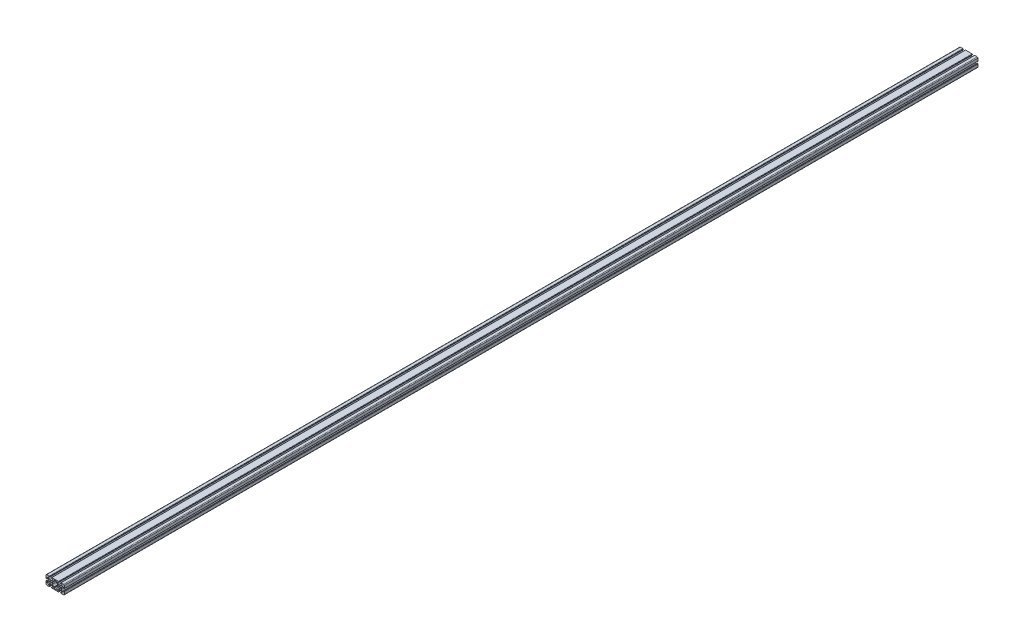
SolidWorks part; units mm, degrees
material "6061 Alloy"
ref_plane "Front Plane" through (0, 0, 0) normal (0, 0, 1) x (1, 0, 0)
ref_plane "Top Plane" through (0, 0, 0) normal (0, 1, 0) x (1, 0, 0)
ref_plane "Right Plane" through (0, 0, 0) normal (1, 0, 0) x (0, 0, -1)
sketch "Sketch1" plane through (0, 0, 0) normal (0, 0, 1) x (1, 0, 0)
  line L0 (-14.3719, 20) -> (14.3719, 20)
  line L1 (-15.94, 17.1729) -> (-15.94, 18.3529)
  line L2 (-11.285, 15.68) -> (-14.37, 15.68)
  line L3 (-9.715, 13.6545) -> (-9.715, 14.11)
  line L4 (4.0718, 15.68) -> (-4.0718, 15.68)
  line L5 (-5.3418, 14.41) -> (-5.3418, 12.1296)
  line L6 (-5.7137, 11.2316) -> (-10.5988, 6.3465)
  line L7 (-12.2841, 3.2591) -> (-12.2841, -2.725)
  line L8 (5.991, -20) -> (-1.7801, -20)
  line L9 (0, 20) -> (0, -25.1394) construction
  line L10 (-4.0718, -15.68) -> (4.0718, -15.68)
  line L11 (-5.3418, -12.1296) -> (-5.3418, -14.41)
  line L12 (-11.2012, -5.7441) -> (-5.7137, -11.2316)
  line L13 (-42.275, 0) -> (43.1806, 0) construction
  line L14 (-9.9376, 13.1171) -> (-14.0919, 8.9628)
  line L15 (-17.4506, 7.7) -> (-22.5494, 7.7)
  line L16 (-25.9081, 8.9628) -> (-30.0624, 13.1171)
  line L17 (-30.285, 13.6545) -> (-30.285, 14.11)
  line L18 (-28.715, 15.68) -> (-25.63, 15.68)
  line L19 (-24.06, 17.25) -> (-24.06, 18.4312)
  line L20 (-25.5696, 20) -> (-33, 20)
  line L21 (-33, 20) -> (-36.83, 20)
  line L22 (-40, 16.8406) -> (-40, 13.0106)
  line L23 (-40, 13.0106) -> (-40, 5.5825)
  line L24 (-38.3243, 4.06) -> (-37.1443, 4.06)
  line L25 (-35.68, 5.6264) -> (-35.68, 8.7114)
  line L26 (-34.11, 10.2814) -> (-33.6509, 10.2814)
  line L27 (-33.1135, 10.0588) -> (-29.0111, 5.9564)
  line L28 (-27.7159, 2.571) -> (-27.7159, -2.502)
  line L29 (-28.9155, -5.8608) -> (-33.1719, -10.1172)
  line L30 (-33.7093, -10.3398) -> (-34.111, -10.3398)
  line L31 (-35.68, -8.715) -> (-35.68, -5.63)
  line L32 (-37.25, -4.06) -> (-38.43, -4.06)
  line L33 (-40, -5.5696) -> (-40, -13)
  line L34 (-40, -13) -> (-40, -16.83)
  line L35 (-37.0574, -20) -> (-33.2274, -20)
  line L36 (-33.2274, -20) -> (-25.797, -20)
  line L37 (-24.06, -18.4389) -> (-24.06, -17.25)
  line L38 (-25.63, -15.68) -> (-28.715, -15.68)
  line L39 (-30.285, -14.11) -> (-30.285, -13.6545)
  line L40 (-30.0624, -13.1171) -> (-26.3095, -9.3642)
  line L41 (-23.3415, -7.7) -> (-16.6585, -7.7)
  line L42 (-13.6905, -9.3642) -> (-9.9376, -13.1171)
  line L43 (-9.715, -13.6545) -> (-9.715, -14.11)
  line L44 (-11.285, -15.68) -> (-14.37, -15.68)
  line L45 (-15.94, -17.25) -> (-15.94, -18.43)
  line L46 (-14.37, -20) -> (-5.991, -20)
  line L47 (-5.991, -20) -> (-1.7801, -20)
  line L48 (14.37, -20) -> (5.991, -20)
  line L49 (15.94, -17.25) -> (15.94, -18.43)
  line L50 (11.285, -15.68) -> (14.37, -15.68)
  line L51 (9.715, -13.6545) -> (9.715, -14.11)
  line L52 (13.6905, -9.3642) -> (9.9376, -13.1171)
  line L53 (23.3415, -7.7) -> (16.6585, -7.7)
  line L54 (30.0624, -13.1171) -> (26.3095, -9.3642)
  line L55 (30.285, -14.11) -> (30.285, -13.6545)
  line L56 (25.63, -15.68) -> (28.715, -15.68)
  line L57 (24.06, -18.4389) -> (24.06, -17.25)
  line L58 (33.2274, -20) -> (25.797, -20)
  line L59 (37.0574, -20) -> (33.2274, -20)
  line L60 (40, -13) -> (40, -16.83)
  line L61 (40, -5.5696) -> (40, -13)
  line L62 (37.25, -4.06) -> (38.43, -4.06)
  line L63 (35.68, -8.715) -> (35.68, -5.63)
  line L64 (33.7093, -10.3398) -> (34.111, -10.3398)
  line L65 (28.9155, -5.8608) -> (33.1719, -10.1172)
  line L66 (27.7159, 2.571) -> (27.7159, -2.502)
  line L67 (33.1135, 10.0588) -> (29.0111, 5.9564)
  line L68 (34.11, 10.2814) -> (33.6509, 10.2814)
  line L69 (35.68, 5.6264) -> (35.68, 8.7114)
  line L70 (38.3243, 4.06) -> (37.1443, 4.06)
  line L71 (40, 13.0106) -> (40, 5.5825)
  line L72 (40, 16.8406) -> (40, 13.0106)
  line L73 (33, 20) -> (36.83, 20)
  line L74 (25.5696, 20) -> (33, 20)
  line L75 (24.06, 17.25) -> (24.06, 18.4312)
  line L76 (28.715, 15.68) -> (25.63, 15.68)
  line L77 (30.285, 13.6545) -> (30.285, 14.11)
  line L78 (25.9081, 8.9628) -> (30.0624, 13.1171)
  line L79 (17.4506, 7.7) -> (22.5494, 7.7)
  line L80 (9.9376, 13.1171) -> (14.0919, 8.9628)
  line L81 (11.2012, -5.7441) -> (5.7137, -11.2316)
  line L82 (5.3418, -12.1296) -> (5.3418, -14.41)
  line L83 (12.2841, 3.2591) -> (12.2841, -2.725)
  line L84 (5.7137, 11.2316) -> (10.5988, 6.3465)
  line L85 (5.3418, 14.41) -> (5.3418, 12.1296)
  line L86 (9.715, 13.6545) -> (9.715, 14.11)
  line L87 (11.285, 15.68) -> (14.37, 15.68)
  line L88 (15.94, 17.1729) -> (15.94, 18.3529)
  line L89 (-20, 24.8708) -> (-20, -18.43) construction
  line L90 (20, 29.4355) -> (20, -23.1087) construction
  line L91 (-3.0962, 16.9038) -> (-43.6857, -23.6857) construction
  line L92 (-36.2671, 16.2671) -> (-2.7875, -17.2125) construction
  arc A0 (-15.94, 18.3529) -> (-14.3719, 20) centre (-14.3719, 18.43) cw
  circle A1 centre (-20, 0) radius 3.4
  arc A2 (-14.37, 15.68) -> (-15.94, 17.1729) centre (-14.3719, 17.25) cw
  arc A3 (-11.285, 15.68) -> (-9.715, 14.11) centre (-11.285, 14.11) cw
  arc A4 (-9.715, 13.6545) -> (-9.9376, 13.1171) centre (-10.475, 13.6545) cw
  arc A5 (-12.2841, -2.725) -> (-11.2012, -5.7441) centre (-7.5341, -2.725) ccw
  arc A6 (-4.0718, 15.68) -> (-5.3418, 14.41) centre (-4.0718, 14.41) ccw
  arc A7 (-5.7137, 11.2316) -> (-5.3418, 12.1296) centre (-6.6118, 12.1296) ccw
  arc A8 (-10.5988, 6.3465) -> (-12.2841, 3.2591) centre (-7.5685, 2.6887) ccw
  arc A9 (-5.3418, -14.41) -> (-4.0718, -15.68) centre (-4.0718, -14.41) ccw
  arc A10 (-5.3418, -12.1296) -> (-5.7137, -11.2316) centre (-6.6118, -12.1296) ccw
  arc A11 (-17.4506, 7.7) -> (-14.0919, 8.9628) centre (-17.3191, 12.4482) ccw
  arc A12 (-25.9081, 8.9628) -> (-22.5494, 7.7) centre (-22.6809, 12.4482) ccw
  arc A13 (-30.285, 13.6545) -> (-30.0624, 13.1171) centre (-29.525, 13.6545) ccw
  arc A14 (-28.715, 15.68) -> (-30.285, 14.11) centre (-28.715, 14.11) ccw
  arc A15 (-25.63, 15.68) -> (-24.06, 17.25) centre (-25.63, 17.25) ccw
  arc A16 (-24.06, 18.4312) -> (-25.5696, 20) centre (-25.63, 18.4312) ccw
  arc A17 (-36.83, 20) -> (-40, 16.8406) centre (-36.83, 16.83) ccw
  arc A18 (-40, 5.5825) -> (-38.3243, 4.06) centre (-38.4306, 5.6264) ccw
  arc A19 (-37.1443, 4.06) -> (-35.68, 5.6264) centre (-37.25, 5.6264) ccw
  arc A20 (-34.11, 10.2814) -> (-35.68, 8.7114) centre (-34.11, 8.7114) ccw
  arc A21 (-33.1135, 10.0588) -> (-33.6509, 10.2814) centre (-33.6509, 9.5214) ccw
  arc A22 (-27.7159, 2.571) -> (-29.0111, 5.9564) centre (-32.4643, 2.6948) ccw
  arc A23 (-28.9155, -5.8608) -> (-27.7159, -2.502) centre (-32.4617, -2.7006) ccw
  arc A24 (-33.7093, -10.3398) -> (-33.1719, -10.1172) centre (-33.7093, -9.5798) ccw
  arc A25 (-35.68, -8.715) -> (-34.111, -10.3398) centre (-34.111, -8.7698) ccw
  arc A26 (-35.68, -5.63) -> (-37.25, -4.06) centre (-37.25, -5.63) ccw
  arc A27 (-38.43, -4.06) -> (-40, -5.5696) centre (-38.4312, -5.63) ccw
  arc A28 (-40, -16.83) -> (-37.0574, -20) centre (-36.83, -16.8382) ccw
  arc A29 (-25.797, -20) -> (-24.06, -18.4389) centre (-25.63, -18.4389) ccw
  arc A30 (-24.06, -17.25) -> (-25.63, -15.68) centre (-25.63, -17.25) ccw
  arc A31 (-30.285, -14.11) -> (-28.715, -15.68) centre (-28.715, -14.11) ccw
  arc A32 (-30.0624, -13.1171) -> (-30.285, -13.6545) centre (-29.525, -13.6545) ccw
  arc A33 (-23.3415, -7.7) -> (-26.3095, -9.3642) centre (-22.6565, -12.4003) ccw
  arc A34 (-13.6905, -9.3642) -> (-16.6585, -7.7) centre (-17.3435, -12.4003) ccw
  arc A35 (-9.715, -13.6545) -> (-9.9376, -13.1171) centre (-10.475, -13.6545) ccw
  arc A36 (-11.285, -15.68) -> (-9.715, -14.11) centre (-11.285, -14.11) ccw
  arc A37 (-14.37, -15.68) -> (-15.94, -17.25) centre (-14.37, -17.25) ccw
  arc A38 (-15.94, -18.43) -> (-14.37, -20) centre (-14.37, -18.43) ccw
  arc A39 (15.94, -18.43) -> (14.37, -20) centre (14.37, -18.43) cw
  arc A40 (14.37, -15.68) -> (15.94, -17.25) centre (14.37, -17.25) cw
  arc A41 (11.285, -15.68) -> (9.715, -14.11) centre (11.285, -14.11) cw
  arc A42 (9.715, -13.6545) -> (9.9376, -13.1171) centre (10.475, -13.6545) cw
  arc A43 (13.6905, -9.3642) -> (16.6585, -7.7) centre (17.3435, -12.4003) cw
  arc A44 (23.3415, -7.7) -> (26.3095, -9.3642) centre (22.6565, -12.4003) cw
  arc A45 (30.0624, -13.1171) -> (30.285, -13.6545) centre (29.525, -13.6545) cw
  arc A46 (30.285, -14.11) -> (28.715, -15.68) centre (28.715, -14.11) cw
  arc A47 (24.06, -17.25) -> (25.63, -15.68) centre (25.63, -17.25) cw
  arc A48 (25.797, -20) -> (24.06, -18.4389) centre (25.63, -18.4389) cw
  arc A49 (40, -16.83) -> (37.0574, -20) centre (36.83, -16.8382) cw
  arc A50 (38.43, -4.06) -> (40, -5.5696) centre (38.4312, -5.63) cw
  arc A51 (35.68, -5.63) -> (37.25, -4.06) centre (37.25, -5.63) cw
  arc A52 (35.68, -8.715) -> (34.111, -10.3398) centre (34.111, -8.7698) cw
  arc A53 (33.7093, -10.3398) -> (33.1719, -10.1172) centre (33.7093, -9.5798) cw
  arc A54 (28.9155, -5.8608) -> (27.7159, -2.502) centre (32.4617, -2.7006) cw
  arc A55 (27.7159, 2.571) -> (29.0111, 5.9564) centre (32.4643, 2.6948) cw
  arc A56 (33.1135, 10.0588) -> (33.6509, 10.2814) centre (33.6509, 9.5214) cw
  arc A57 (34.11, 10.2814) -> (35.68, 8.7114) centre (34.11, 8.7114) cw
  arc A58 (37.1443, 4.06) -> (35.68, 5.6264) centre (37.25, 5.6264) cw
  arc A59 (40, 5.5825) -> (38.3243, 4.06) centre (38.4306, 5.6264) cw
  arc A60 (36.83, 20) -> (40, 16.8406) centre (36.83, 16.83) cw
  arc A61 (24.06, 18.4312) -> (25.5696, 20) centre (25.63, 18.4312) cw
  arc A62 (25.63, 15.68) -> (24.06, 17.25) centre (25.63, 17.25) cw
  arc A63 (28.715, 15.68) -> (30.285, 14.11) centre (28.715, 14.11) cw
  arc A64 (30.285, 13.6545) -> (30.0624, 13.1171) centre (29.525, 13.6545) cw
  arc A65 (25.9081, 8.9628) -> (22.5494, 7.7) centre (22.6809, 12.4482) cw
  arc A66 (17.4506, 7.7) -> (14.0919, 8.9628) centre (17.3191, 12.4482) cw
  arc A67 (5.3418, -12.1296) -> (5.7137, -11.2316) centre (6.6118, -12.1296) cw
  arc A68 (5.3418, -14.41) -> (4.0718, -15.68) centre (4.0718, -14.41) cw
  arc A69 (10.5988, 6.3465) -> (12.2841, 3.2591) centre (7.5685, 2.6887) cw
  arc A70 (5.7137, 11.2316) -> (5.3418, 12.1296) centre (6.6118, 12.1296) cw
  arc A71 (4.0718, 15.68) -> (5.3418, 14.41) centre (4.0718, 14.41) cw
  arc A72 (12.2841, -2.725) -> (11.2012, -5.7441) centre (7.5341, -2.725) cw
  arc A73 (9.715, 13.6545) -> (9.9376, 13.1171) centre (10.475, 13.6545) ccw
  arc A74 (11.285, 15.68) -> (9.715, 14.11) centre (11.285, 14.11) ccw
  arc A75 (14.37, 15.68) -> (15.94, 17.1729) centre (14.3719, 17.25) ccw
  circle A76 centre (20, 0) radius 3.4
  arc A77 (15.94, 18.3529) -> (14.3719, 20) centre (14.3719, 18.43) ccw
  dimension "D4" = 6.8
  dimension "D1" = 80
  dimension "D2" = 40
  dimension "D3" = 20
  dimension "D5" = 8.12
  dimension "D6" = 4.32
  dimension "D7" = 20.57
  dimension "D8" = 4.32
  dimension "D9" = 8.12
  dimension "D10" = 12.3
  dimension "D11" = 4.32
  dimension "D12" = 4.32
  dimension "D13" = 4.32
extrude "Extrude1" add sketch "Sketch1" against normal blind 4000
